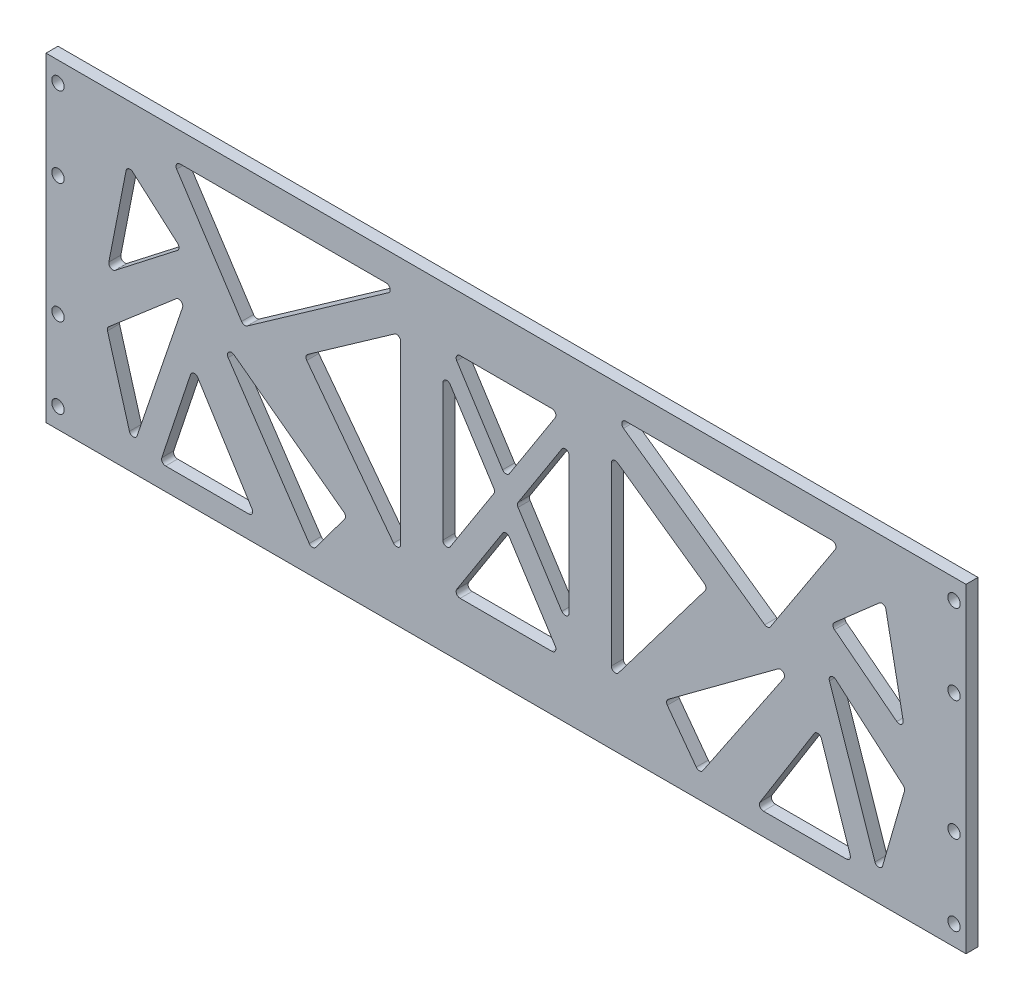
SolidWorks part; units mm, degrees
ref_plane "前视基准面" through (0, 0, 0) normal (0, 0, 1) x (1, 0, 0)
ref_plane "上视基准面" through (0, 0, 0) normal (0, 1, 0) x (1, 0, 0)
ref_plane "右视基准面" through (0, 0, 0) normal (1, 0, 0) x (0, 0, -1)
sketch "草图1" plane through (0, 0, 0) normal (0, 0, 1) x (1, 0, 0)
  line L1 (-115, 40) -> (115, 40)
  line L2 (-115, 40) -> (-115, -40)
  line L3 (-115, -40) -> (115, -40)
  line L4 (115, 40) -> (115, -40)
  line L5 (-115, 40) -> (115, -40) construction
  line L6 (-115, -40) -> (115, 40) construction
  point P0 (0, 0)
  dimension "D1" = 230
  dimension "D2" = 80
extrude "凸台-拉伸1" add sketch "草图1" along normal blind 3
sketch "草图2" plane through (0, 0, 3) normal (0, 0, 1) x (1, 0, 0)
  line L0 (-115, 40) -> (-112, 40) construction
  line L1 (115, 40) -> (-115, 40) construction
  line L2 (-112, 40) -> (-112, 35) construction
  circle A0 centre (-112, 35) radius 1.55
  circle A1 centre (-112, 15) radius 1.55
  circle A2 centre (-112, -15) radius 1.55
  circle A3 centre (-112, -35) radius 1.55
  dimension "D3" = 3.1
  dimension "D1" = 3
  dimension "D2" = 5
  dimension "D4" = 2
  dimension "D5" = 2
  dimension "D6" = 2
extrude "切除-拉伸1" cut sketch "草图2" against normal blind 3
mirror "镜向1" about plane through (0, 0, 0) normal (1, 0, 0) of "切除-拉伸1"
sketch "草图3" plane through (0, 0, 3) normal (0, 0, 1) x (1, 0, 0)
  line L0 (-13.3051, 26.2758) -> (13.3051, 26.2758)
  line L1 (-18.7964, 29.2758) -> (18.7964, 29.2758)
  line L2 (-18.7964, 29.2758) -> (-18.7964, -29.2758)
  line L3 (-18.7964, -29.2758) -> (18.7964, -29.2758)
  line L4 (18.7964, 29.2758) -> (18.7964, -29.2758)
  line L5 (-18.7964, 29.2758) -> (18.7964, -29.2758) construction
  line L6 (-18.7964, -29.2758) -> (18.7964, 29.2758) construction
  line L7 (13.3051, 26.2758) -> (0, 5.5527)
  line L8 (0, 5.5527) -> (-13.3051, 26.2758)
  line L9 (115, 40) -> (-115, 40) construction
  line L10 (0, 0) -> (50.6776, 0) construction
  line L11 (0, 0) -> (0, 68.0732) construction
  line L12 (-15.7964, 21.6459) -> (-15.7964, -19.2386)
  line L13 (-15.7964, -19.2386) -> (-2.6715, 1.2036)
  line L14 (-2.6715, 1.2036) -> (-15.7964, 21.6459)
  line L15 (13.3051, -26.2758) -> (0, -5.5527)
  line L16 (-13.3051, -26.2758) -> (13.3051, -26.2758)
  line L17 (0, -5.5527) -> (-13.3051, -26.2758)
  line L18 (15.7964, -19.2386) -> (2.6715, 1.2036)
  line L19 (15.7964, 21.6459) -> (15.7964, -19.2386)
  line L20 (2.6715, 1.2036) -> (15.7964, 21.6459)
  point P0 (0, 0)
  dimension "D1" = 3
  dimension "D2" = 3
  dimension "D3" = 3
extrude "切除-拉伸3" cut sketch "草图3" against normal blind 3 contours L8 L0 L7 | L14 L12 L13 | L15 L17 L16 | L18 L20 L19
fillet "圆角1" radius 1 12 edges at (-15.7964, -19.2386, 1.5) (-2.6715, 1.2036, 1.5) (-15.7964, 21.6459, 1.5) (0, -5.5527, 1.5) (13.3051, -26.2758, 1.5) (-13.3051, -26.2758, 1.5) (15.7964, -19.2386, 1.5) (2.6715, 1.2036, 1.5) (15.7964, 21.6459, 1.5) (13.3051, 26.2758, 1.5) (0, 5.5527, 1.5) (-13.3051, 26.2758, 1.5)
sketch "草图4" plane through (0, 0, 3) normal (0, 0, 1) x (1, 0, 0)
  line L0 (-94.6473, 26.2817) -> (-99.8038, 0)
  line L1 (-99.8038, 0) -> (-81.1738, 14.4716)
  line L2 (-81.1738, 14.4716) -> (-94.6473, 26.2817)
  line L3 (-83.3362, 32.7689) -> (-26.7807, 32.7689)
  line L4 (-26.7807, 32.7689) -> (-65.5378, 5.4892)
  line L5 (-65.5378, 5.4892) -> (-83.3362, 32.7689)
  line L6 (-79.6767, 5.4892) -> (-99.8038, -11.8101)
  line L7 (-99.8038, -11.8101) -> (-93.2565, -34.5018)
  line L8 (-93.2565, -34.5018) -> (-79.6767, 5.4892)
  line L9 (-72.6905, 1.6634) -> (-39.7394, -22.7241)
  line L10 (-39.7394, -22.7241) -> (-48.4049, -34.4323)
  line L11 (-48.4049, -34.4323) -> (-72.6905, 1.6634)
  line L12 (-78.1797, -9.4585) -> (-86.4943, -34.4323)
  line L13 (-86.4943, -34.4323) -> (-62.5437, -34.4323)
  line L14 (-62.5437, -34.4323) -> (-78.1797, -9.4585)
  line L15 (-50.4322, 6.8827) -> (-26.3193, 23.8549)
  line L16 (-26.3193, 23.8549) -> (-26.3193, -25.009)
  line L17 (-26.3193, -25.009) -> (-50.4322, 6.8827)
  point P17 (-79.6767, 5.4892)
  point P19 (-99.8038, -11.8101)
  point P20 (-41.9176, -17.2993)
  point P21 (-62.5437, -34.4323)
  point P22 (-81.1738, 14.4716)
  point P23 (-65.5378, 5.4892)
  point P24 (-43.2483, -20.1271)
  point P25 (-48.4049, -34.4323)
extrude "切除-拉伸4" cut sketch "草图4" against normal blind 3
fillet "圆角2" radius 1 18 edges at (-26.3193, -25.009, 1.5) (-50.4322, 6.8827, 1.5) (-26.3193, 23.8549, 1.5) (-93.2565, -34.5018, 1.5) (-79.6767, 5.4892, 1.5) (-99.8038, -11.8101, 1.5) (-86.4943, -34.4323, 1.5) (-78.1797, -9.4585, 1.5) (-62.5437, -34.4323, 1.5) (-72.6905, 1.6634, 1.5) (-48.4049, -34.4323, 1.5) (-39.7394, -22.7241, 1.5) (-26.7807, 32.7689, 1.5) (-83.3362, 32.7689, 1.5) (-65.5378, 5.4892, 1.5) (-81.1738, 14.4716, 1.5) (-94.6473, 26.2817, 1.5) (-99.8038, 0, 1.5)
mirror "镜向2" about plane through (0, 0, 0) normal (1, 0, 0) of "圆角2", "切除-拉伸4"
